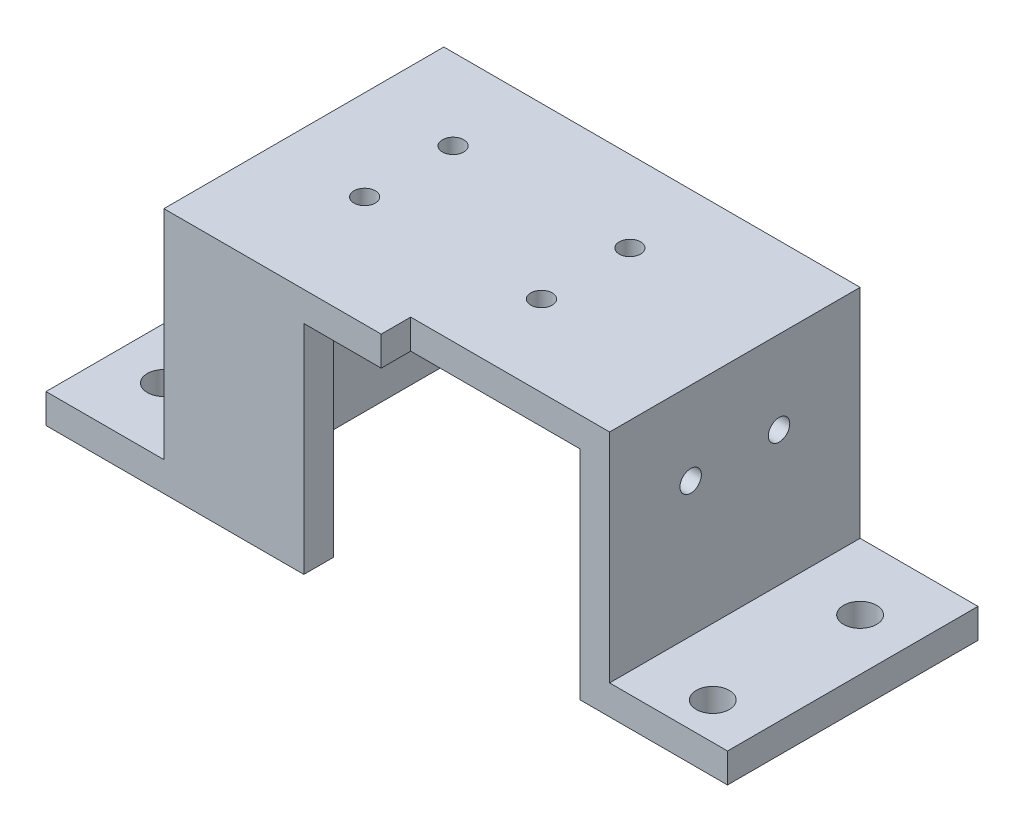
SolidWorks part; units mm, degrees
ref_plane "정면" through (0, 0, 0) normal (0, 0, 1) x (1, 0, 0)
ref_plane "윗면" through (0, 0, 0) normal (0, 1, 0) x (1, 0, 0)
ref_plane "우측면" through (0, 0, 0) normal (1, 0, 0) x (0, 0, -1)
sketch "스케치31" plane through (0, 0, 0) normal (0, 1, 0) x (1, 0, 0)
  line L1 (-28.25, 19) -> (28.25, 19)
  line L2 (-28.25, 19) -> (-28.25, -19)
  line L3 (-28.25, -19) -> (28.25, -19)
  line L4 (28.25, 19) -> (28.25, -19)
  line L5 (-28.25, 19) -> (28.25, -19) construction
  line L6 (-28.25, -19) -> (28.25, 19) construction
  point P0 (0, 0)
  dimension "D1" = 56.5
  dimension "D2" = 38
extrude "보스-돌출11" add sketch "스케치31" along normal blind 4
sketch "스케치32" plane through (0, 0, 0) normal (0, -1, 0) x (1, 0, 0)
  line L0 (28.25, -19) -> (-28.25, -19) construction
  line L1 (28.25, 19) -> (24.25, 19)
  line L2 (28.25, 19) -> (28.25, -19)
  line L3 (28.25, -19) -> (24.25, -19)
  line L4 (24.25, 19) -> (24.25, -19)
  line L6 (-28.25, 19) -> (-24.25, 19)
  line L7 (-28.25, 19) -> (-28.25, -19)
  line L8 (-28.25, -19) -> (-24.25, -19)
  line L9 (-24.25, 19) -> (-24.25, -19)
  dimension "D1" = 4
  dimension "D2" = 4
extrude "보스-돌출12" add sketch "스케치32" along normal blind 29.5
sketch "스케치33" plane through (0, -29.5, 0) normal (0, -1, 0) x (1, 0, 0)
  line L0 (0, 0) -> (0, 23.6607) construction
  line L1 (-28.25, 19) -> (-44.25, 19)
  line L2 (-28.25, 19) -> (-28.25, -19)
  line L3 (-28.25, -19) -> (-44.25, -19)
  line L4 (-44.25, 19) -> (-44.25, -19)
  line L5 (28.25, -19) -> (44.25, -19)
  line L6 (44.25, 19) -> (44.25, -19)
  line L7 (28.25, 19) -> (44.25, 19)
  line L8 (28.25, 19) -> (28.25, -19)
  dimension "D1" = 16
extrude "보스-돌출13" add sketch "스케치33" against normal blind 4
sketch "스케치34" plane through (0, 0, 0) normal (0, -1, 0) x (1, 0, 0)
  line L5 (-24.25, 19) -> (-9.25, 19)
  line L6 (-24.25, 19) -> (-24.25, 15)
  line L7 (-24.25, 15) -> (-9.25, 15)
  line L8 (-9.25, 19) -> (-9.25, 15)
  dimension "D1" = 4
  dimension "D2" = 15
extrude "보스-돌출14" add sketch "스케치34" along normal up to surface (29.5 mm away) up to face at (-34.25, -29.5, 0)
hole_wizard "M2.5 여유 구멍1" positions "스케치38" profile "스케치39" hole size "M2.5" standard "ISO"
sketch "스케치38" plane through (0, 4, 0) normal (0, 1, 0) x (1, 0, 0)
  line L2 (-4, 27.2808) -> (-4, 9.8456) construction
  line L4 (5.5473, 2) -> (18.3975, 2) construction
  line L6 (28.25, 19) -> (-28.25, 19) construction
  point P0 (8, 8)
  point P9 (8, -4)
  point P13 (-16, -4)
  point P14 (-16, 8)
  dimension "D1" = 17
  dimension "D2" = 16.25
  dimension "D3" = 12
  dimension "D4" = 6
  dimension "D5" = 6
sketch "스케치39" plane through (8, 4, -8) normal (1, 0, 0) x (0, 0, 1)
  line L0 (0, 0) -> (0, 10.8712)
  line L1 (0, 10.8712) -> (1.45, 10)
  line L2 (1.45, 10) -> (1.45, 0)
  line L5 (1.45, 0) -> (0, 0)
  line L10 (0, 10.8712) -> (-1.45, 10) construction
  line L11 (0, -6.35) -> (0, 107.95) construction
  dimension "구멍 지름" = 2.9
  dimension "구멍 깊이" = 10
  dimension "드릴 각도" = 118
hole_wizard "M2.5 여유 구멍2" positions "스케치40" profile "스케치41" hole size "M2.5" standard "ISO"
sketch "스케치40" plane through (28.25, 0, 0) normal (1, 0, 0) x (0, 0, -1)
  line L4 (-15, -29.5) -> (-15, 0) construction
  line L5 (-15, -29.5) -> (-15, 0) construction
  line L8 (19, -29.5) -> (-15, -29.5) construction
  line L9 (19, -29.5) -> (-15, -29.5) construction
  line L11 (8, -23.25) -> (-4, -23.25) construction
  line L12 (8, -23.25) -> (8, -7.25) construction
  line L13 (8, -7.25) -> (-4, -7.25) construction
  line L14 (-4, -23.25) -> (-4, -7.25) construction
  line L15 (8, -23.25) -> (-4, -7.25) construction
  line L16 (8, -7.25) -> (-4, -23.25) construction
  point P0 (-4, -7.25)
  point P22 (8, -7.25)
  dimension "D1" = 11
  dimension "D2" = 22.25
  dimension "D3" = 16
  dimension "D4" = 12
sketch "스케치41" plane through (28.25, -7.25, 4) normal (0, 1, 0) x (0, 0, -1)
  line L0 (0, 0) -> (0, 10.8712)
  line L1 (0, 10.8712) -> (1.45, 10)
  line L2 (1.45, 10) -> (1.45, 0)
  line L5 (1.45, 0) -> (0, 0)
  line L10 (0, 10.8712) -> (-1.45, 10) construction
  line L11 (0, -6.35) -> (0, 107.95) construction
  dimension "구멍 지름" = 2.9
  dimension "구멍 깊이" = 10
  dimension "드릴 각도" = 118
hole_wizard "M2.5 여유 구멍3" positions "스케치42" profile "스케치43" hole size "M2.5" standard "ISO"
sketch "스케치42" plane through (-28.25, 0, 0) normal (-1, 0, 0) x (0, 0, 1)
  circle A0 centre (-8, -7.25) radius 1.45 construction
  circle A1 centre (4, -7.25) radius 1.45 construction
  circle A2 centre (-8, -7.25) radius 1.45 construction
  circle A3 centre (4, -7.25) radius 1.45 construction
  point P0 (4, -7.25)
  point P13 (-8, -7.25)
sketch "스케치43" plane through (-28.25, -7.25, 4) normal (0, 1, 0) x (0, 0, 1)
  line L0 (0, 0) -> (0, 10.8712)
  line L1 (0, 10.8712) -> (1.45, 10)
  line L2 (1.45, 10) -> (1.45, 0)
  line L5 (1.45, 0) -> (0, 0)
  line L10 (0, 10.8712) -> (-1.45, 10) construction
  line L11 (0, -6.35) -> (0, 107.95) construction
  dimension "구멍 지름" = 2.9
  dimension "구멍 깊이" = 10
  dimension "드릴 각도" = 118
hole_wizard "M4 여유 구멍1" positions "스케치44" profile "스케치45" hole size "M4" standard "ISO"
sketch "스케치44" plane through (0, -25.5, 0) normal (0, 1, 0) x (1, 0, 0)
  line L0 (32.1, 0) -> (50.23, 0) construction
  line L2 (44.25, 19) -> (44.25, -19) construction
  line L3 (0, 0) -> (0, 26.7589) construction
  line L4 (-24.25, 19) -> (-24.25, -15) construction
  line L5 (-24.25, 19) -> (-24.25, -15)
  line L6 (-12, 17.3353) -> (-12, -15)
  line L8 (28.25, 19) -> (44.25, 19) construction
  point P0 (37.25, 10)
  point P10 (37.25, -10)
  point P14 (-37.25, -10)
  point P15 (-37.25, 10)
  dimension "D1" = 10
  dimension "D2" = 7
  dimension "D3" = 61.5
  dimension "D4" = 12.25
  dimension "D5" = 49.25
  dimension "D6" = 9
sketch "스케치45" plane through (37.25, -25.5, -10) normal (1, 0, 0) x (0, 0, 1)
  line L0 (0, 0) -> (0, 11.3519)
  line L1 (0, 11.3519) -> (2.25, 10)
  line L2 (2.25, 10) -> (2.25, 0)
  line L5 (2.25, 0) -> (0, 0)
  line L10 (0, 11.3519) -> (-2.25, 10) construction
  line L11 (0, -6.35) -> (0, 107.95) construction
  dimension "구멍 지름" = 4.5
  dimension "구멍 깊이" = 10
  dimension "드릴 각도" = 118
sketch "스케치46" plane through (0, 0, 19) normal (0, 0, 1) x (1, 0, 0)
  line L0 (-28.25, 4) -> (28.25, 4) construction
  line L1 (44.25, -29.5) -> (1.25, -29.5)
  line L2 (44.25, -29.5) -> (44.25, 4)
  line L3 (44.25, 4) -> (1.25, 4)
  line L4 (1.25, -29.5) -> (1.25, 4)
  dimension "D1" = 43
extrude "컷-돌출4" cut sketch "스케치46" against normal blind 4
